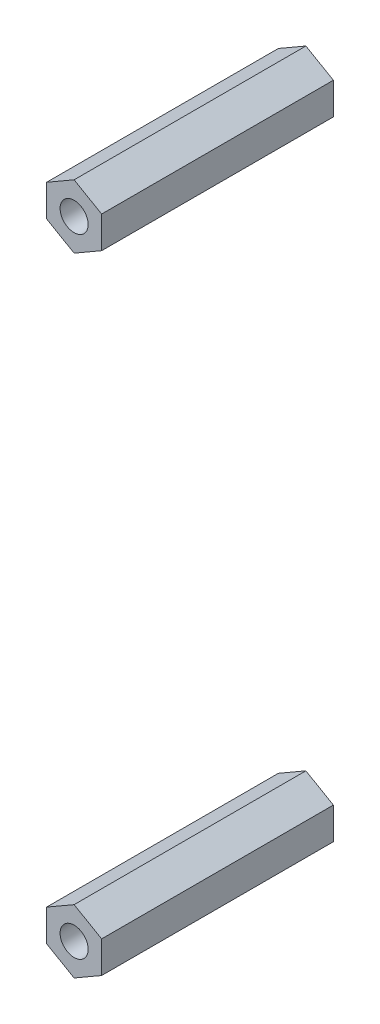
SolidWorks part; units mm, degrees
material "6061-T6 (SS)"
ref_plane "Front Plane" through (0, 0, 0) normal (0, 0, 1) x (1, 0, 0)
ref_plane "Top Plane" through (0, 0, 0) normal (0, 1, 0) x (1, 0, 0)
ref_plane "Right Plane" through (0, 0, 0) normal (1, 0, 0) x (0, 0, -1)
ref_plane "Plane4" through (0, 0, 37.846) normal (0, 0, 1) x (1, 0, 0)
sketch "Sketch1" plane through (0, 0, 37.846) normal (0, 0, 1) x (1, 0, 0)
  line L6 (-33.4772, 104.2545) -> (-33.4772, 111.6455)
  line L7 (-33.4772, 111.6455) -> (-39.878, 115.341)
  line L8 (-39.878, 115.341) -> (-46.2788, 111.6455)
  line L9 (-46.2788, 111.6455) -> (-46.2788, 104.2545)
  line L10 (-46.2788, 104.2545) -> (-39.878, 100.559)
  line L11 (-39.878, 100.559) -> (-33.4772, 104.2545)
  line L12 (-33.4772, 104.2545) -> (-33.4772, 111.6455)
  line L13 (-33.4772, 111.6455) -> (-39.878, 115.341)
  line L14 (-39.878, 115.341) -> (-46.2788, 111.6455)
  line L15 (-46.2788, 111.6455) -> (-46.2788, 104.2545)
  line L16 (-46.2788, 104.2545) -> (-39.878, 100.559)
  line L17 (-39.878, 100.559) -> (-33.4772, 104.2545)
  line L18 (-33.4772, -34.4045) -> (-39.878, -30.709)
  line L19 (-39.878, -30.709) -> (-46.2788, -34.4045)
  line L20 (-46.2788, -34.4045) -> (-46.2788, -41.7955)
  line L21 (-46.2788, -41.7955) -> (-39.878, -45.491)
  line L22 (-39.878, -45.491) -> (-33.4772, -41.7955)
  line L23 (-33.4772, -41.7955) -> (-33.4772, -34.4045)
  line L24 (-33.4772, -34.4045) -> (-39.878, -30.709)
  line L25 (-39.878, -30.709) -> (-46.2788, -34.4045)
  line L26 (-46.2788, -34.4045) -> (-46.2788, -41.7955)
  line L27 (-46.2788, -41.7955) -> (-39.878, -45.491)
  line L28 (-39.878, -45.491) -> (-33.4772, -41.7955)
  line L29 (-33.4772, -41.7955) -> (-33.4772, -34.4045)
  circle A0 centre (-39.878, -38.1) radius 3.2639 construction
  circle A1 centre (-39.878, 107.95) radius 3.2639 construction
  circle A2 centre (-39.878, -38.1) radius 3.2639
  circle A3 centre (-39.878, 107.95) radius 3.2639
  dimension "D1" = 0
  dimension "D2" = 0
extrude "Boss-Extrude1" add sketch "Sketch1" along normal up to surface (53.9242 mm away)
